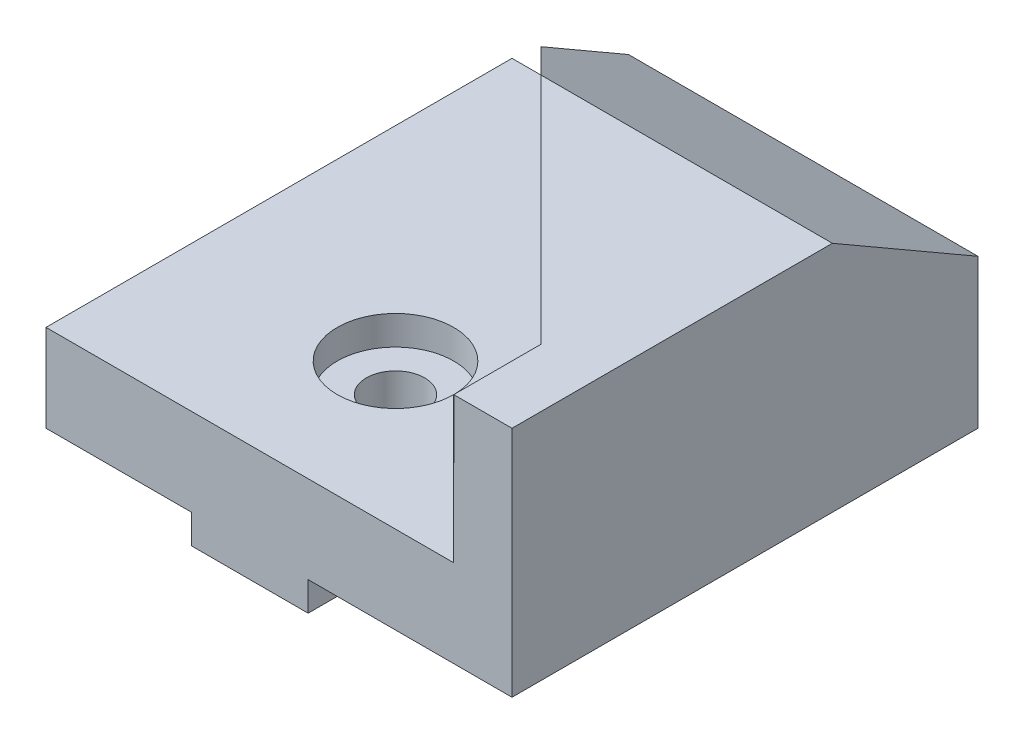
SolidWorks part; units mm, degrees
ref_plane "Front Plane" through (0, 0, 0) normal (0, 0, 1) x (1, 0, 0)
ref_plane "Top Plane" through (0, 0, 0) normal (0, 1, 0) x (1, 0, 0)
ref_plane "Right Plane" through (0, 0, 0) normal (1, 0, 0) x (0, 0, -1)
sketch "Sketch1" plane through (0, 0, 0) normal (0, 0, 1) x (1, 0, 0)
  line L1 (0, 5) -> (25, 5)
  line L2 (25, 5) -> (25, 0)
  line L3 (25, 0) -> (45, 0)
  line L4 (45, 0) -> (45, 5)
  line L5 (45, 5) -> (80, 5)
  line L6 (80, 5) -> (80, 45)
  line L7 (0, 5) -> (0, 20)
  line L8 (0, 20) -> (20, 20)
  line L9 (20, 20) -> (20, 45)
  line L10 (20, 45) -> (80, 45)
  point P0 (0, 0)
  dimension "D1" = 20
  dimension "D2" = 15
  dimension "D3" = 40
  dimension "D4" = 80
  dimension "D5" = 20
  dimension "D6" = 25
  dimension "D7" = 20
extrude "Boss-Extrude1" add sketch "Sketch1" along normal blind 80
sketch "Sketch2" plane through (0, 45, 0) normal (0, 1, 0) x (1, 0, 0)
  line L1 (80, -80) -> (20, -80) construction
  line L2 (70, -80) -> (70, -65)
  line L3 (70, -65) -> (20, -15)
  line L8 (70, -80) -> (20, -80)
  line L9 (20, -80) -> (20, -15)
  line L10 (20, -80) -> (20, 0) construction
  dimension "D1" = 45
  dimension "D2" = 15
  dimension "D3" = 10
extrude "Cut-Extrude1" cut sketch "Sketch2" against normal blind 25
sketch "Sketch3" plane through (20, 0, 0) normal (-1, 0, 0) x (0, 0, 1)
  line L0 (80, 20) -> (80, 45) construction
  line L1 (65, 45) -> (15, 45) construction
  line L2 (25, 45) -> (0, 30.5662)
  line L3 (25, 45) -> (0, 45)
  line L4 (0, 45) -> (0, 30.5662)
  dimension "D1" = 55
  dimension "D2" = 30
extrude "Cut-Extrude2" cut sketch "Sketch3" against normal through all
sketch "Sketch4" plane through (0, 20, 0) normal (0, 1, 0) x (1, 0, 0)
  line L0 (0, -80) -> (0, 0) construction
  line L1 (70, -80) -> (0, -80) construction
  circle A0 centre (35, -55) radius 5
  dimension "D1" = 10
  dimension "D2" = 35
  dimension "D3" = 25
extrude "Cut-Extrude3" cut sketch "Sketch4" against normal through all
sketch "Sketch5" plane through (0, 20, 0) normal (0, 1, 0) x (1, 0, 0)
  circle A0 centre (35, -55) radius 10
  dimension "D1" = 20
extrude "Cut-Extrude5" cut sketch "Sketch5" against normal blind 5
